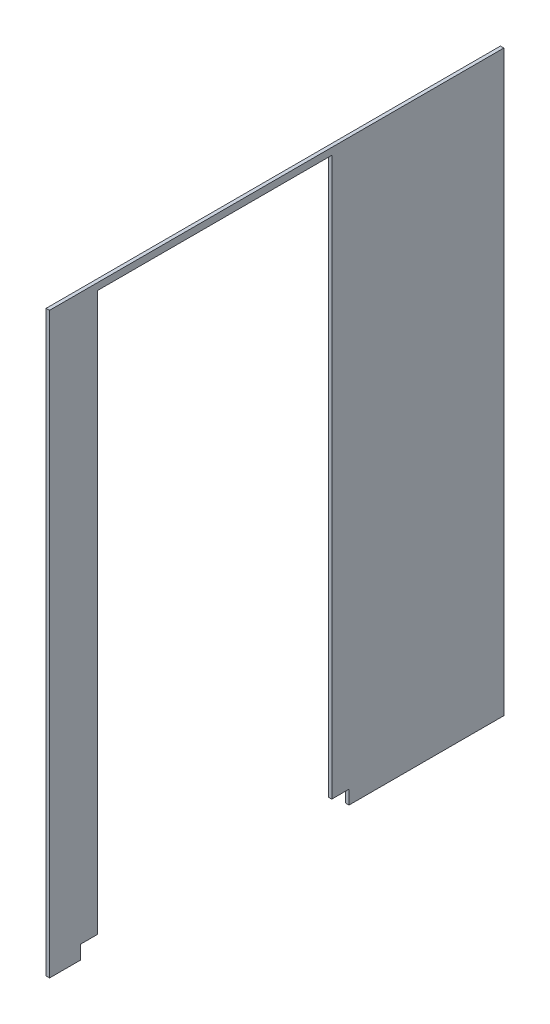
SolidWorks part; units mm, degrees
ref_plane "Front Plane" through (0, 0, 0) normal (0, 0, 1) x (1, 0, 0)
ref_plane "Top Plane" through (0, 0, 0) normal (0, 1, 0) x (1, 0, 0)
ref_plane "Right Plane" through (0, 0, 0) normal (1, 0, 0) x (0, 0, -1)
sketch "Sketch1" plane through (0, 0, 0) normal (1, 0, 0) x (0, 0, -1)
  line L0 (0, 0) -> (114.3, 0)
  line L2 (0, 0) -> (0, 2133.6)
  line L3 (0, 2133.6) -> (1676.4, 2133.6)
  line L4 (1676.4, 0) -> (1676.4, 2133.6)
  line L5 (114.3, 0) -> (114.3, 50.8)
  line L6 (114.3, 50.8) -> (177.8, 50.8)
  line L7 (177.8, 50.8) -> (177.8, 2108.2)
  line L8 (177.8, 2108.2) -> (1041.4, 2108.2)
  line L9 (1041.4, 2108.2) -> (1041.4, 50.8)
  line L10 (1041.4, 50.8) -> (1104.9, 50.8)
  line L11 (1104.9, 50.8) -> (1104.9, 0)
  line L12 (1104.9, 0) -> (1676.4, 0)
  dimension "D1" = 1676.4
  dimension "D2" = 2133.6
  dimension "D3" = 114.3
  dimension "D4" = 50.8
  dimension "D5" = 63.5
  dimension "D6" = 2057.4
  dimension "D7" = 2057.4
  dimension "D8" = 571.5
  dimension "D9" = 863.6
  dimension "D10" = 63.5
  dimension "D11" = 50.8
extrude "Boss-Extrude1" add sketch "Sketch1" along normal blind 12.7
